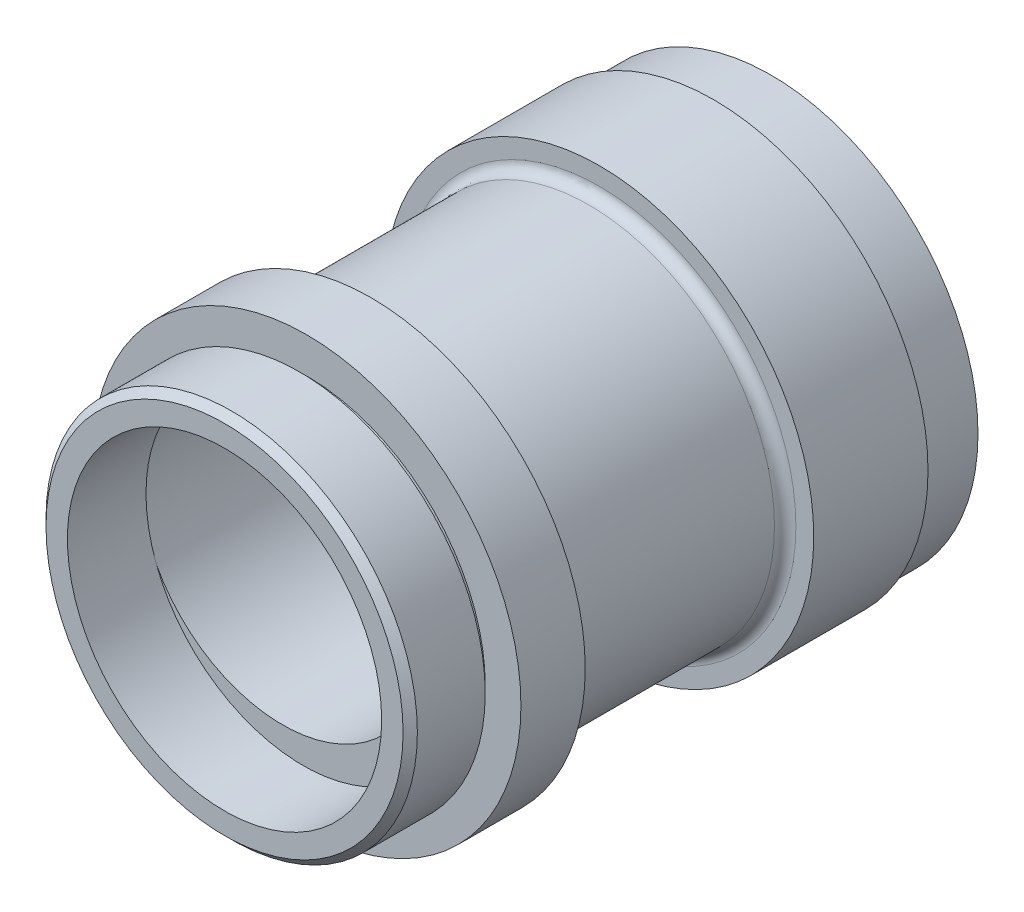
SolidWorks part; units mm, degrees
ref_plane "Plan de face" through (0, 0, 0) normal (0, 0, 1) x (1, 0, 0)
ref_plane "Plan de dessus" through (0, 0, 0) normal (0, 1, 0) x (1, 0, 0)
ref_plane "Plan de droite" through (0, 0, 0) normal (1, 0, 0) x (0, 0, -1)
sketch "Sketch1" plane through (0, 0, 0) normal (0, 0, 1) x (1, 0, 0)
  circle A0 centre (0, 0) radius 14.5
  dimension "D1" = 29
extrude "Boss-Extrude1" add sketch "Sketch1" along normal blind 4
sketch "Sketch2" plane through (0, 0, 4) normal (0, 0, 1) x (1, 0, 0)
  circle A0 centre (0, 0) radius 15
  dimension "D1" = 30
extrude "Boss-Extrude2" add sketch "Sketch2" along normal blind 8
sketch "Sketch3" plane through (0, 0, 12) normal (0, 0, 1) x (1, 0, 0)
  circle A0 centre (0, 0) radius 13
  dimension "D1" = 26
extrude "Boss-Extrude3" add sketch "Sketch3" along normal blind 16
sketch "Sketch4" plane through (0, 0, 28) normal (0, 0, 1) x (1, 0, 0)
  circle A0 centre (0, 0) radius 15
  dimension "D1" = 30
extrude "Boss-Extrude4" add sketch "Sketch4" along normal blind 4.5
sketch "Sketch5" plane through (0, 0, 32.5) normal (0, 0, 1) x (1, 0, 0)
  circle A0 centre (0, 0) radius 12.5
  dimension "D1" = 25
extrude "Boss-Extrude5" add sketch "Sketch5" along normal blind 0.5
sketch "Sketch6" plane through (0, 0, 33) normal (0, 0, 1) x (1, 0, 0)
  circle A0 centre (0, 0) radius 13
  dimension "D1" = 26
extrude "Boss-Extrude6" add sketch "Sketch6" along normal blind 5.25
cosmetic thread "Cosmetic Thread1" parameters "D2"=25
sketch "Sketch7" plane through (0, 0, 38.25) normal (0, 0, 1) x (1, 0, 0)
  circle A0 centre (0, 0) radius 11
  dimension "D1" = 22
extrude "Cut-Extrude1" cut sketch "Sketch7" against normal blind 5.5
sketch "Sketch8" plane through (0, 0, 32.75) normal (0, 0, 1) x (1, 0, 0)
  circle A0 centre (-1.44, 0.75) radius 10
  circle A1 centre (0, 0) radius 15 construction
  dimension "D1" = 20
  dimension "D2" = 0.75
  dimension "D3" = 1.44
other "AlignGroup1"
extrude "Cut-Extrude2" cut sketch "Sketch8" against normal blind 32.75 contours A0
fillet "Fillet1" radius 0.75 2 edges at (13, 0, 12) (13, 0, 28)
chamfer "Chamfer1" distance 0.5 angle 45 1 edges at (13, 0, 38.25)
sketch "Sketch14" plane through (0, 0, 0) normal (0, 0, -1) x (-1, 0, 0)
  circle A0 centre (-9.5, 8.8) radius 1
  point P0 (-9.5, 8.8)
  dimension "D1" = 9.5
  dimension "D4" = 2
  dimension "D2" = 8.8
hole_wizard "Ø2.0 (2) Diameter Hole3" positions "Sketch14" profile "Sketch15" hole size "Ø2.0" standard "ISO"
sketch "Sketch15" plane through (9.5, 8.8, 0) normal (1, 0, 0) x (0, 1, 0)
  line L0 (0, 0) -> (0, 9.25)
  line L1 (0, 9.25) -> (1, 8.6491)
  line L2 (1, 8.6491) -> (1, 0)
  line L5 (1, 0) -> (0, 0)
  line L10 (0, 9.25) -> (-1, 8.6491) construction
  line L11 (0, -6.35) -> (0, 107.95) construction
  dimension "Hole Dia." = 2
  dimension "Hole Depth" = 9.25
  dimension "Drill Angle" = 118
